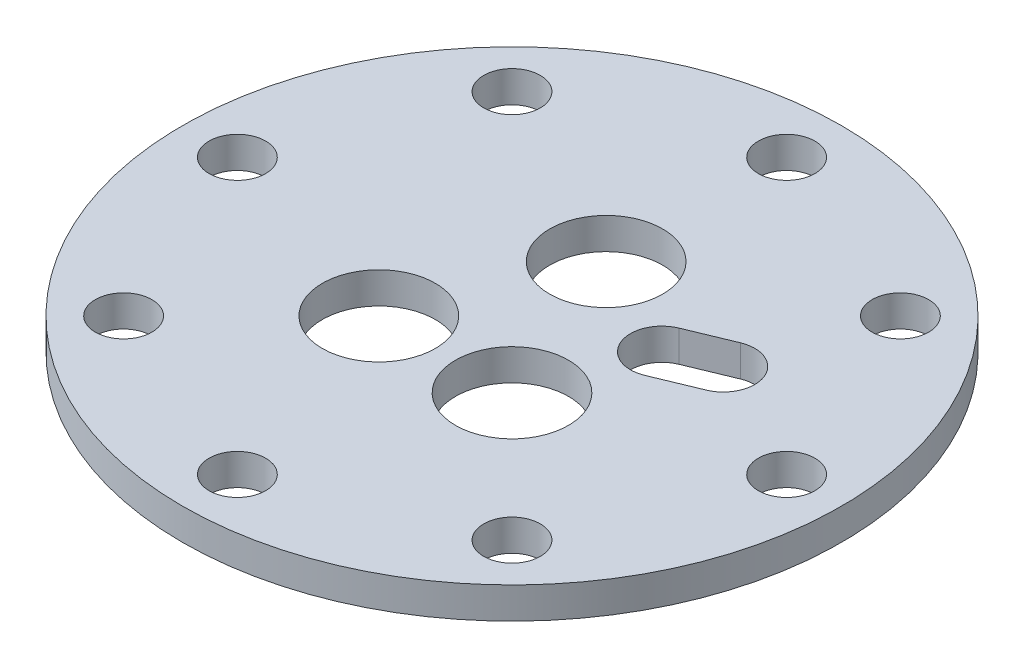
SolidWorks part; units mm, degrees
ref_plane "Front Plane" through (0, 0, 0) normal (0, 0, 1) x (1, 0, 0)
ref_plane "Top Plane" through (0, 0, 0) normal (0, 1, 0) x (1, 0, 0)
ref_plane "Right Plane" through (0, 0, 0) normal (1, 0, 0) x (0, 0, -1)
sketch "Sketch2" plane through (0, 0, 0) normal (0, 1, 0) x (1, 0, 0)
  line L0 (0, 0) -> (0, 105) construction
  line L1 (0, 0) -> (145.9568, 0) construction
  line L2 (0, 0) -> (37.2246, 15.419) construction
  line L3 (51.4451, 10.4853) -> (37.5869, 4.7451)
  line L4 (43.7915, 28.9629) -> (29.9333, 23.2227)
  line L5 (38.3795, 15.8973) -> (148.1275, 61.3564) construction
  circle A0 centre (0, 0) radius 105
  circle A1 centre (0, 87.5) radius 9
  circle A2 centre (61.8718, 61.8718) radius 9
  circle A3 centre (0, 30) radius 10.2
  circle A4 centre (87.5, 0) radius 9
  circle A5 centre (61.8718, -61.8718) radius 9
  circle A6 centre (0, -87.5) radius 9
  circle A7 centre (-61.8718, -61.8718) radius 9
  circle A8 centre (-87.5, 0) radius 9
  circle A9 centre (-61.8718, 61.8718) radius 9
  circle A12 centre (0, 0) radius 50
  circle A13 centre (0, 30) radius 13
  circle A14 centre (21.2132, -21.2132) radius 18
  circle A15 centre (21.2132, -21.2132) radius 10.2
  circle A16 centre (33.7601, 13.9839) radius 3.75
  circle A17 centre (0, 30) radius 18
  circle A18 centre (21.2132, -21.2132) radius 13
  circle A19 centre (-21.2132, -21.2132) radius 18
  circle A20 centre (-21.2132, -21.2132) radius 10.2
  circle A21 centre (-21.2132, -21.2132) radius 13
  arc A22 (29.9333, 23.2227) -> (37.5869, 4.7451) centre (33.7601, 13.9839) ccw
  arc A23 (51.4451, 10.4853) -> (43.7915, 28.9629) centre (47.6183, 19.7241) ccw
  point P3 (0, 87.5)
  point P8 (0, 0)
  point P11 (0, 30)
  point P23 (0, 0)
  point P29 (0, 0)
  point P30 (0, 0)
  point P33 (0, 0)
  point P34 (0, 0)
  point P36 (0, 0)
  point P44 (0, 0)
  point P49 (0, 0)
  point P50 (33.7601, 13.9839)
  dimension "D1" = 210
  dimension "D4" = 18
  dimension "D5" = 100
  dimension "D7" = 20.4
  dimension "D8" = 26
  dimension "D9" = 2
  dimension "D12" = 20
  dimension "D14" = 7.5
  dimension "D15" = 36
  dimension "D16" = 15
  dimension "D11" = 20
  dimension "D2" = 17.5
  dimension "D6" = 30
  dimension "D13" = 22.5
  dimension "D3" = 8
  dimension "D10" = 2
sketch "Sketch3" plane through (0, 0, 0) normal (0, 1, 0) x (1, 0, 0)
  line L0 (51.4451, 10.4853) -> (37.5869, 4.7451) construction
  line L2 (51.4451, 10.4853) -> (37.5869, 4.7451)
  line L3 (43.7915, 28.9629) -> (29.9333, 23.2227)
  arc A0 (51.4451, 10.4853) -> (43.7915, 28.9629) centre (47.6183, 19.7241) ccw construction
  circle A7 centre (61.8718, 61.8718) radius 9
  circle A8 centre (61.8718, 61.8718) radius 9
  circle A9 centre (0, 87.5) radius 9
  circle A10 centre (0, 87.5) radius 9
  circle A11 centre (0, 0) radius 105
  circle A12 centre (0, 0) radius 105
  circle A13 centre (-61.8718, 61.8718) radius 9
  circle A14 centre (-61.8718, 61.8718) radius 9
  circle A15 centre (-87.5, 0) radius 9
  circle A16 centre (-87.5, 0) radius 9
  circle A17 centre (-61.8718, -61.8718) radius 9
  circle A18 centre (-61.8718, -61.8718) radius 9
  circle A19 centre (0, -87.5) radius 9
  circle A20 centre (0, -87.5) radius 9
  circle A21 centre (61.8718, -61.8718) radius 9
  circle A22 centre (61.8718, -61.8718) radius 9
  circle A23 centre (87.5, 0) radius 9
  circle A24 centre (87.5, 0) radius 9
  circle A31 centre (0, 30) radius 18
  circle A32 centre (0, 30) radius 18
  circle A37 centre (21.2132, -21.2132) radius 18
  circle A38 centre (21.2132, -21.2132) radius 18
  circle A39 centre (-21.2132, -21.2132) radius 18
  circle A40 centre (-21.2132, -21.2132) radius 18
  arc A41 (29.9333, 23.2227) -> (37.5869, 4.7451) centre (33.7601, 13.9839) ccw construction
  arc A42 (51.4451, 10.4853) -> (43.7915, 28.9629) centre (47.6183, 19.7241) ccw
  arc A43 (29.9333, 23.2227) -> (37.5869, 4.7451) centre (33.7601, 13.9839) ccw
  dimension "D4" = 0
  dimension "D5" = 0
  dimension "D6" = 0
  dimension "D7" = 0
  dimension "D8" = 0
  dimension "D9" = 0
  dimension "D10" = 0
  dimension "D11" = 0
  dimension "D12" = 0
  dimension "D16" = 0
  dimension "D19" = 0
  dimension "D20" = 0
extrude "Boss-Extrude2" add sketch "Sketch3" along normal blind 10 contours A12 A43 L3 A42 L2 A40 A38 A32 A24 A22 A20 A18 A16 A14 A8 A10
